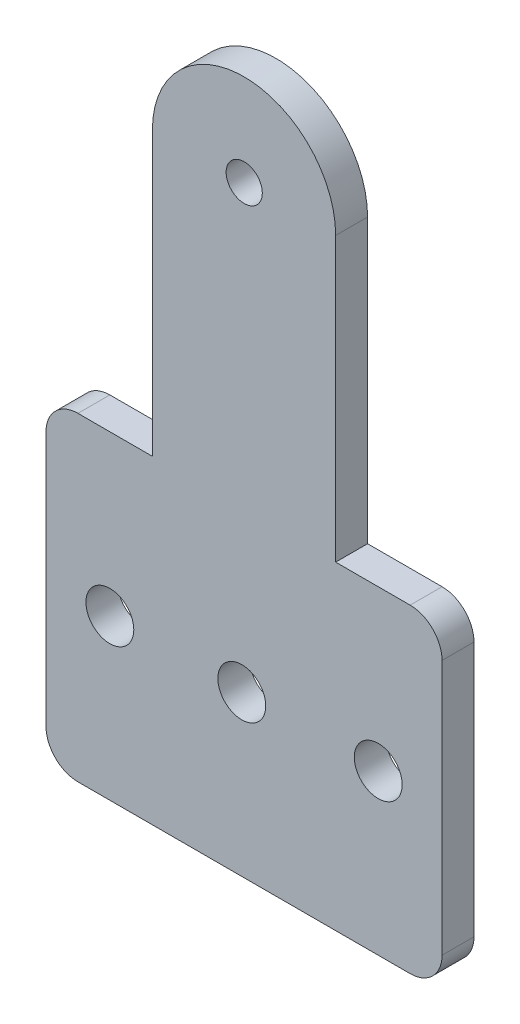
SolidWorks part; units mm, degrees
ref_plane "Front Plane" through (0, 0, 0) normal (0, 0, 1) x (1, 0, 0)
ref_plane "Top Plane" through (0, 0, 0) normal (0, 1, 0) x (1, 0, 0)
ref_plane "Right Plane" through (0, 0, 0) normal (1, 0, 0) x (0, 0, -1)
sketch "Sketch1" plane through (0, 0, 0) normal (0, 0, 1) x (1, 0, 0)
  line L5 (50.7738, 15) -> (50.7738, 41.5958)
  line L6 (50.7738, 15) -> (40.7738, 15)
  line L7 (78, -15) -> (40.7738, -15)
  line L9 (78, -15) -> (78, 15)
  line L13 (68, 15) -> (68, 41.5958)
  line L14 (78, 15) -> (68, 15)
  line L15 (40.7738, -15) -> (40.7738, 15)
  arc A0 (68, 41.5958) -> (50.7738, 41.5958) centre (59.3869, 41.5958) ccw
  point P2 (59.3869, 0)
extrude "Boss-Extrude1" add sketch "Sketch1" along normal blind 3
hole_wizard "M3 Clearance Hole1" positions "Sketch2" profile "Sketch3" hole size "M3" standard "ISO" end condition through all
sketch "Sketch2" plane through (0, 0, 3) normal (0, 0, 1) x (1, 0, 0)
  point P0 (59.4035, 41.5958)
sketch "Sketch3" plane through (59.4035, 41.5958, 3) normal (1, 0, 0) x (0, -1, 0)
  line L0 (0, 0) -> (0, 3)
  line L1 (0, 3) -> (1.7, 3)
  line L2 (1.7, 3) -> (1.7, 0)
  line L5 (1.7, 0) -> (0, 0)
  line L11 (0, -6.35) -> (0, 107.95) construction
  dimension "Thru Hole Dia." = 3.4
  dimension "Thru Hole Depth" = 3
hole_wizard "M4 Clearance Hole1" positions "Sketch4" profile "Sketch5" hole size "M4" standard "ISO" end condition through all
sketch "Sketch4" plane through (0, 0, 3) normal (0, 0, 1) x (1, 0, 0)
  line L0 (792, 0) -> (0, 0) construction
  line L1 (40.7738, 15) -> (40.7738, -15) construction
  line L2 (78, -15) -> (78, 15) construction
  line L3 (59.1771, -15) -> (59.1771, 15) construction
  line L4 (40.7738, -15) -> (78, -15) construction
  line L5 (59.1771, 15) -> (50.7738, 15) construction
  point P0 (46.7738, 0)
  point P4 (72, 0)
  point P6 (59.1771, 0)
  dimension "D1" = 6
  dimension "D2" = 6
sketch "Sketch5" plane through (46.7738, 0, 3) normal (1, 0, 0) x (0, -1, 0)
  line L0 (0, 0) -> (0, 3)
  line L1 (0, 3) -> (2.25, 3)
  line L2 (2.25, 3) -> (2.25, 0)
  line L5 (2.25, 0) -> (0, 0)
  line L11 (0, -6.35) -> (0, 107.95) construction
  dimension "Thru Hole Dia." = 4.5
  dimension "Thru Hole Depth" = 3
fillet "Fillet1" radius 3 4 edges at (78, -15, 1.5) (40.7738, -15, 1.5) (40.7738, 15, 1.5) (78, 15, 1.5)
equation "\"D2@Sketch4\"=\"D1@Sketch4\""
